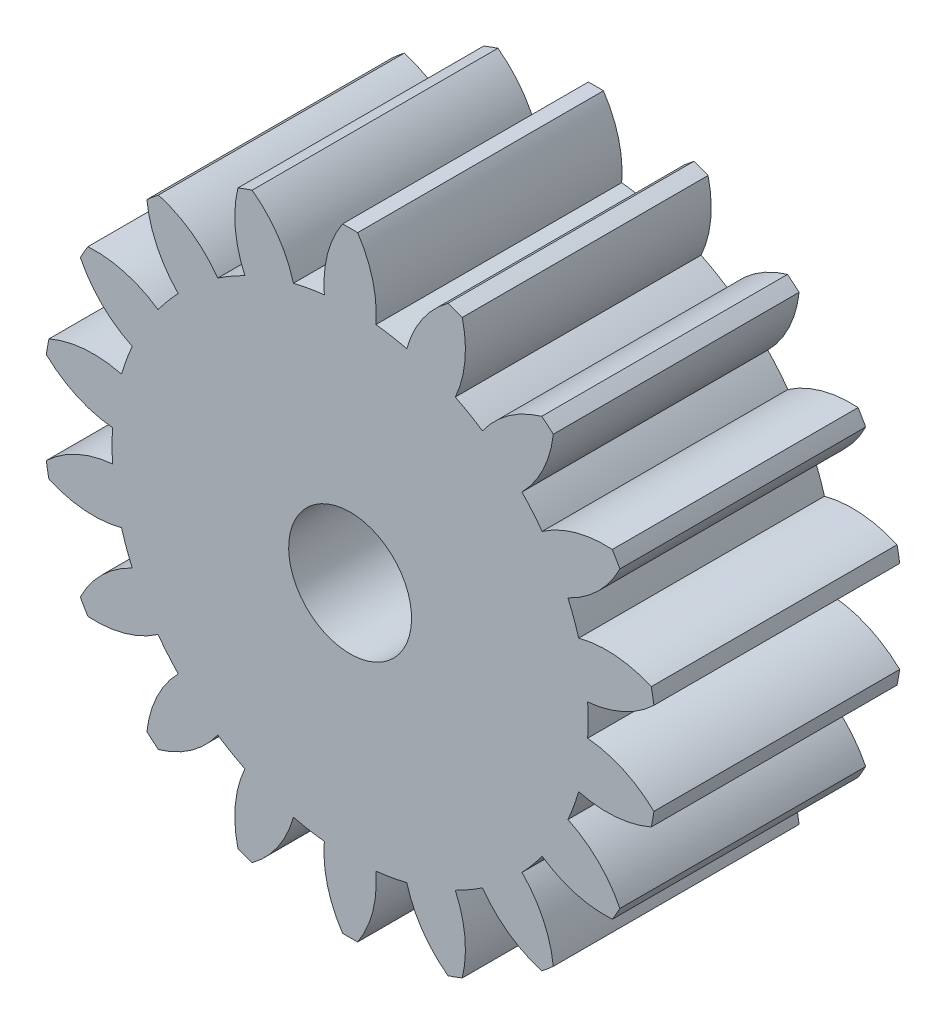
SolidWorks part; units mm, degrees
material "Alumina"
ref_plane "Plane1" through (0, 0, 0) normal (0, 0, 1) x (1, 0, 0)
ref_plane "Plane2" through (0, 0, 0) normal (0, 1, 0) x (1, 0, 0)
ref_plane "Plane3" through (0, 0, 0) normal (1, 0, 0) x (0, 0, -1)
sketch "HoldingSke" plane through (0, 0, 0) normal (0, 1, 0) x (1, 0, 0)
  line L0 (0, 0) -> (1.9021, -0.618)
  line L1 (-15, 0) -> (100, 0) construction
  line L2 (0, 0) -> (-2.1039, 2.3779)
  line L3 (0, 0) -> (-11.863, 4.5341)
  line L4 (0, 0) -> (8.2133, 2.6687)
  line L5 (0, 0) -> (-46.8476, -17.4728)
  line L6 (0, 0) -> (-3.3159, -2.2372)
  line L7 (-2.1039, 2.3779) -> (8.6586, 51.2059)
  line L8 (-76.2, 54.61) -> (-75.7, 54.61)
  line L9 (-71.009, 38.7566) -> (-53.1078, 45.2721)
  line L10 (-76.2, 71.12) -> (104.1128, 71.12)
  line L11 (0, 0) -> (-4, 0)
  line L12 (-76.2, 101.6) -> (-76.181, 101.6)
  line L13 (24.9733, 27.94) -> (52.9518, 28.4284)
  line L14 (24.9733, 27.94) -> (24.9743, 27.94)
  line L15 (24.9733, 27.94) -> (100.4006, 29.5858)
  line L16 (-63.627, -0.5) -> (-12.827, -0.5)
  circle A0 centre (0, 0) radius 1.5
  circle A1 centre (0, 0) radius 3.874
  circle A2 centre (0, 0) radius 37.5
  circle A3 centre (0, 0) radius 1.5
  dimension "MHD" = 7.748
  dimension "Hub_dia" = 75
  dimension "Bore" = 3
  dimension "MBD" = 3
  dimension "Num_teeth" = 18
  dimension "Pitch" = 2
  dimension "Overall_len" = 50
  dimension "Show_teeth" = 18
  dimension "Thickness" = 4
  dimension "OAL" = 50.0001
  dimension "T_dim" = 0.5
  dimension "Ap" = 20
  dimension "H" = 19.05
  dimension "Pitch_radius" = 180.3128
  dimension "Width" = 4
  dimension "Backlash" = 0.019
  dimension "Addendum_fac" = 1
  dimension "Dedendum_fac" = 1.25
  dimension "Clearance_fac" = 0.25
  dimension "Dedendum_add" = 0.001
  dimension "Module" = 0.5
sketch "BasProSke" plane through (0, 0, 0) normal (0, 1, 0) x (1, 0, 0)
  line L0 (-10, 0) -> (60, 0) construction
  line L1 (0, 0) -> (0, 5)
  line L2 (0, 0) -> (4, 0)
  line L3 (4, 0) -> (4, 5)
  line L4 (4, 5) -> (0, 5)
  dimension "Thickness" = 4
  dimension "Diameter" = 10
revolve "Base-Revolve" add sketch "BasProSke" angle 360 about L0
sketch "TooCutSke" plane through (0, 0, 0) normal (1, 0, 0) x (0, 0, -1)
  line L1 (0, 0) -> (0, 107) construction
  line L2 (0, 0) -> (-0.4254, 4.4798) construction
  line L3 (0, 0) -> (-1.5579, 8.835) construction
  line L4 (-0.4254, 4.4798) -> (-0.7789, 4.4175) construction
  arc A0 (0.2553, 3.8656) -> (-0.2553, 3.8656) centre (0, 0) ccw
  arc A1 (0.7686, 4.9663) -> (-0.7686, 4.9663) centre (0, 0) ccw
  circle A2 centre (0, 0) radius 4.5 construction
  circle A3 centre (0, 0) radius 4.2286 construction
  arc A4 (-0.2553, 3.8656) -> (-0.7686, 4.9663) centre (-2.0476, 3.6998) ccw
  arc A5 (0.7686, 4.9663) -> (0.2553, 3.8656) centre (2.0476, 3.6998) ccw
  dimension "Root_dia" = 7.748
  dimension "Overcut_dia" = 10.0508
  dimension "Pitch_dia" = 9
  dimension "Base_dia" = 8.4572
  dimension "Flank_rad" = 1.8
  dimension "Half_ang" = 10
  dimension "Half_CT" = 0.359
extrude "ToothCut" cut sketch "TooCutSke" along normal through all
fillet "Breaks" [suppressed] radius 0.01
fillet "RootFillets" [suppressed] radius 0.126
pattern_circular "TeethCuts" count 18 every 20 about axis through (-10, 0, 0) along (1, 0, 0) of "ToothCut", "RootFillets", "Breaks"
sketch "HubNeaOneSke" plane through (0, 0, 0) normal (-1, 0, 0) x (0, 0, 1)
  circle A0 centre (0, 0) radius 3.874
  dimension "Diameter" = 7.748
extrude "HubNearOne" [suppressed] add sketch "HubNeaOneSke" along normal blind 46.0001
sketch "HubNeaBotSke" plane through (0, 0, 0) normal (-1, 0, 0) x (0, 0, 1)
  circle A0 centre (0, 0) radius 3.874
  dimension "Diameter" = 7.748
extrude "HubNearBoth" [suppressed] add sketch "HubNeaBotSke" along normal blind 23
ref_plane "FarPln" through (4, 0, 0) normal (1, 0, 0) x (0, 0, -1)
sketch "HubFarSke" plane through (4, 0, 0) normal (1, 0, 0) x (0, 0, -1)
  circle A0 centre (0, 0) radius 3.874
  dimension "Diameter" = 7.748
extrude "HubFar" [suppressed] add sketch "HubFarSke" along normal blind 23
sketch "BorSke" plane through (0, 0, 0) normal (1, 0, 0) x (0, 0, -1)
  circle A1 centre (0, 0) radius 1
extrude "Bore" cut sketch "BorSke" along normal mid plane 100.0001
sketch "KeySke" plane through (0, 0, 0) normal (1, 0, 0) x (0, 0, -1)
  line L0 (-0.6, 0) -> (-0.6, 2)
  line L1 (-0.6, 2) -> (0.6, 2)
  line L2 (0.6, 2) -> (0.6, 0)
  line L3 (0, 0) -> (0, 34) construction
  line L4 (-0.6, 0) -> (0.6, 0)
  dimension "Offset" = 2
  dimension "Width" = 1.2
extrude "Keyway" [suppressed] cut sketch "KeySke" along normal mid plane 100.0001
pattern_circular "Keyway2" [suppressed] count 2 every 90 about axis through (-10, 0, 0) along (1, 0, 0)
move or copy body "Body-Move/Copy1" bodies to move or copy 103 copy no rotation origin (2, 0, 0) rotation axis (0, 0, -1) rotation angle 90
move or copy body "Body-Move/Copy2" bodies to move or copy 104 copy no rotation origin (0, 0, 0) rotation axis (-1, 0, 0) rotation angle 90
equation "' \"Module@HoldingSke\" = 6.35"
equation "' \"Num_teeth@HoldingSke\" = 12"
equation "' \"Ap@HoldingSke\" =  20"
equation "' \"Ap@HoldingSke\" = 20"
equation "' \"Width@HoldingSke\" = 0.5 * 25.4"
equation "' \"Hub_dia@HoldingSke\"= 1 * 25.4"
equation "' \"Hub_dia@HoldingSke\" = 1 * 25.4"
equation "' \"Overall_len@HoldingSke\" = 1.0 * 25.4"
equation "' \"Bore@HoldingSke\" = 0.75 * 25.4"
equation "' \"T_dim@HoldingSke\" = 0.1 * 25.4"
equation "' \"Width@KeySke\" = 0.25 * 25.4"
equation "' \"Show_teeth@HoldingSke\" = 13"
equation "' \"Backlash@HoldingSke\" = 0.009 * 25.4"
equation "' \"Addendum_fac@HoldingSke\" = 1.0"
equation "' \"Dedendum_fac@HoldingSke\" = 1.25"
equation "' \"Dedendum_add@HoldingSke\" = 0.00005 * 25.4"
equation "' \"Clearance_fac@HoldingSke\" = 0.25"
equation "\"Pitch@HoldingSke\" = 1 / \"Module@HoldingSke\""
equation "\"Overcut_dia@TooCutSke\" = (\"Num_teeth@HoldingSke\" + 2 * \"Addendum_fac@HoldingSke\") / \"Pitch@HoldingSke\" + 0.002 * 25.4"
equation "\"Pitch_dia@TooCutSke\" = \"Num_teeth@HoldingSke\" / \"Pitch@HoldingSke\""
equation "\"Base_dia@TooCutSke\" = \"Num_teeth@HoldingSke\" / \"Pitch@HoldingSke\" * cos((\"Ap@HoldingSke\"  * 3.14159265 / 180))"
equation "\"Root_dia@TooCutSke\" = (\"Num_teeth@HoldingSke\" + 2) / \"Pitch@HoldingSke\" - 2 * (\"Addendum_fac@HoldingSke\" + \"Dedendum_fac@HoldingSke\") / \"Pitch@HoldingSke\" - \"Dedendum_add@HoldingSke\" * 2"
equation "\"Half_ang@TooCutSke\" = 180 / \"Num_teeth@HoldingSke\""
equation "\"Half_CT@TooCutSke\" = \"Num_teeth@HoldingSke\" / \"Pitch@HoldingSke\" * sin((3.14159265 / 2 / \"Num_teeth@HoldingSke\")) / 2 - 7 * \"Backlash@HoldingSke\" / 4"
equation "\"Flank_rad@TooCutSke\" = \"Num_teeth@HoldingSke\" / \"Pitch@HoldingSke\" / 5"
equation "\"Radius@RootFillets\" = \"Clearance_fac@HoldingSke\" / \"Pitch@HoldingSke\" + \"Dedendum_add@HoldingSke\""
equation "\"Break_rad@Breaks\" = 0.02 / \"Pitch@HoldingSke\""
equation "\"Thickness@HoldingSke\" = \"Width@HoldingSke\""
equation "\"OAL@HoldingSke\" = \"Thickness@HoldingSke\""
equation "\"MHD@HoldingSke\" = (\"Num_teeth@HoldingSke\" + 2) / \"Pitch@HoldingSke\" - 2 * (\"Addendum_fac@HoldingSke\" + \"Dedendum_fac@HoldingSke\")  / \"Pitch@HoldingSke\" - \"Dedendum_add@HoldingSke\" * 2"
equation "\"MBD@HoldingSke\" = (\"Num_teeth@HoldingSke\" + 2) / \"Pitch@HoldingSke\" - 2 * (\"Addendum_fac@HoldingSke\" + \"Dedendum_fac@HoldingSke\")  / \"Pitch@HoldingSke\" - \"Dedendum_add@HoldingSke\" * 2 - 0.002 * 25.4"
equation "\"MHD@HoldingSke\" = ((sgn( \"MHD@HoldingSke\" - \"Hub_dia@HoldingSke\" )-1)*( \"MHD@HoldingSke\" - \"Hub_dia@HoldingSke\" ))/-2+ \"Hub_dia@HoldingSke\""
equation "\"MBD@HoldingSke\" = ((sgn( \"MBD@HoldingSke\" - \"Bore@HoldingSke\" )-1)*( \"MBD@HoldingSke\" - \"Bore@HoldingSke\" ))/-2+ \"Bore@HoldingSke\""
equation "\"OAL@HoldingSke\" = ((sgn( \"OAL@HoldingSke\" - \"Overall_len@HoldingSke\" )+1)*( \"OAL@HoldingSke\" - \"Overall_len@HoldingSke\" ))/2 + \"Overall_len@HoldingSke\" + 0.000002 * 25.4"
equation "\"Num_teeth@TeethCuts\" = int( \"Show_teeth@HoldingSke\" ) + 1"
equation "\"Num_teeth@TeethCuts\" = ((sgn( \"Num_teeth@TeethCuts\" - \"Num_teeth@HoldingSke\" )-1)*( \"Num_teeth@TeethCuts\" - \"Num_teeth@HoldingSke\" ))/-2+ \"Num_teeth@HoldingSke\""
equation "\"Num_teeth@TeethCuts\" = ((sgn( \"Num_teeth@TeethCuts\" - 2.0)+1)*( \"Num_teeth@TeethCuts\" - 2.0))/2 +2.0"
equation "\"Angle@TeethCuts\" = 360.0 / \"Num_teeth@HoldingSke\""
equation "\"Diameter@BasProSke\" = (\"Num_teeth@HoldingSke\" + 2 * \"Addendum_fac@HoldingSke\") / \"Pitch@HoldingSke\""
equation "\"Thickness@BasProSke\"  = \"Thickness@HoldingSke\""
equation "' \"Fillet_rad@BasProSke\" =  \"Thickness@HoldingSke\" * 0.05"
equation "' \"Fillet_rad@BasProSke\" = \"Thickness@HoldingSke\" * 0.05"
equation "\"MHD@HoldingSke\" = ((sgn( \"MHD@HoldingSke\" - \"Root_dia@TooCutSke\" )-1)*( \"MHD@HoldingSke\" - \"Root_dia@TooCutSke\" ))/-2+ \"Root_dia@TooCutSke\""
equation "\"Diameter@HubNeaOneSke\" = \"MHD@HoldingSke\""
equation "\"Length@HubNearOne\" = \"OAL@HoldingSke\" - \"Thickness@BasProSke\""
equation "\"Diameter@HubNeaBotSke\" = \"MHD@HoldingSke\""
equation "\"Length@HubNearBoth\" = ( \"OAL@HoldingSke\" - \"Thickness@BasProSke\" ) / 2.0"
equation "\"Thickness@FarPln\" = \"Thickness@BasProSke\""
equation "\"Diameter@HubFarSke\" = \"MHD@HoldingSke\""
equation "\"Length@HubFar\" = ( \"OAL@HoldingSke\" - \"Thickness@BasProSke\" ) / 2.0"
equation "\"D1@Bore\" = \"OAL@HoldingSke\" * 2.0"
equation "\"D1@Keyway\" = \"OAL@HoldingSke\" * 2.0"
equation "\"Offset@KeySke\" = \"T_dim@HoldingSke\" + \"MBD@HoldingSke\" / 2.0"
